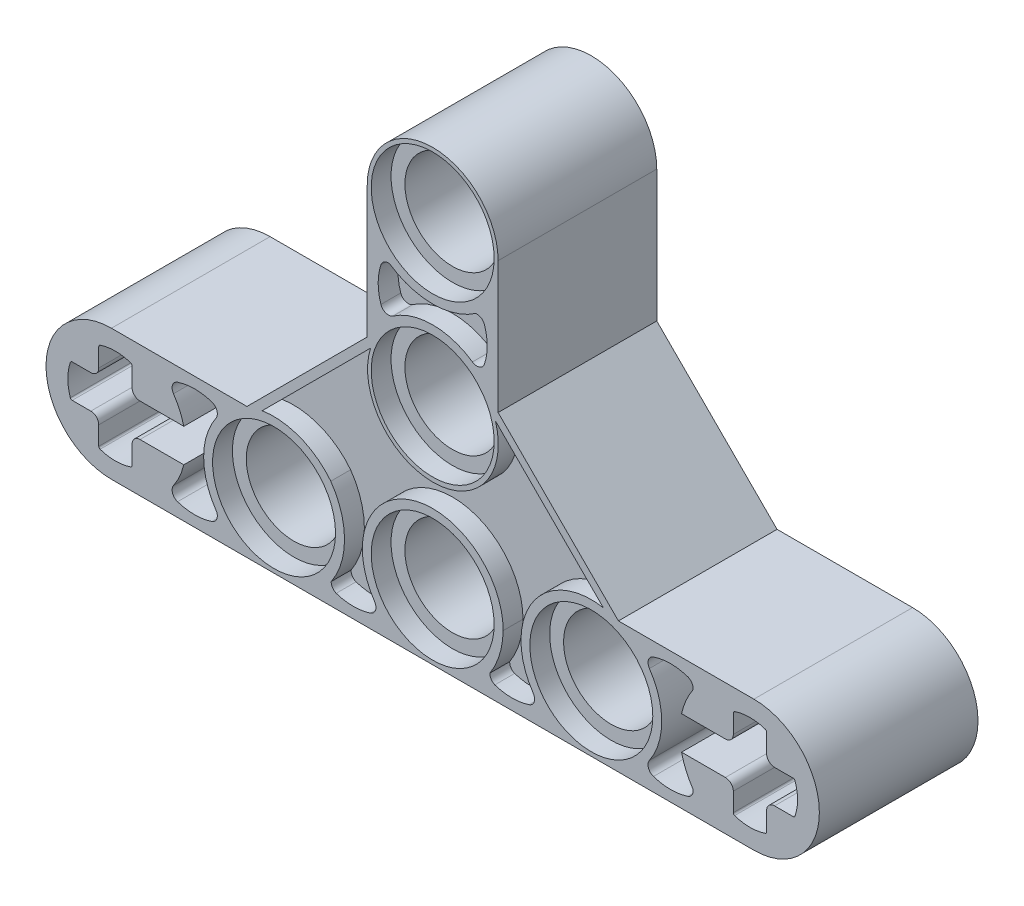
SolidWorks part; units mm, degrees
ref_plane "Front Plane" through (0, 0, 0) normal (0, 0, 1) x (1, 0, 0)
ref_plane "Top Plane" through (0, 0, 0) normal (0, 1, 0) x (1, 0, 0)
ref_plane "Right Plane" through (0, 0, 0) normal (1, 0, 0) x (0, 0, -1)
sketch "Sketch2" plane through (0, 0, 0) normal (0, 0, 1) x (1, 0, 0)
  line L0 (16.2, -3.3) -> (-16.2, -3.3)
  line L2 (16.2, 3.3) -> (9.3669, 3.3)
  line L6 (-17.24, 0.84) -> (-18.1777, 0.84)
  line L7 (-16.84, -2.1777) -> (-16.84, -1.24)
  line L8 (-15.16, -2.1777) -> (-15.16, -1.24)
  line L9 (-16.84, -2.2482) -> (-15.16, 2.2482) construction
  line L10 (-16.84, 2.2482) -> (-15.16, -2.2482) construction
  line L11 (-13.8223, 0.84) -> (-14.76, 0.84)
  line L12 (-13.8223, -0.84) -> (-14.76, -0.84)
  line L13 (-13.7518, 0.84) -> (-18.2482, -0.84) construction
  line L14 (-13.7518, -0.84) -> (-18.2482, 0.84) construction
  line L15 (-16.84, 1.24) -> (-16.84, 2.1777)
  line L16 (-15.16, 1.24) -> (-15.16, 2.1777)
  line L17 (-17.24, -0.84) -> (-18.1777, -0.84)
  line L18 (-13.7518, 0.84) -> (-12.5508, 0.84)
  line L19 (-13.7518, -0.84) -> (-12.5508, -0.84)
  line L20 (-13.8223, -0.84) -> (-13.7518, -0.84)
  line L21 (-13.8223, 0.84) -> (-13.7518, 0.84)
  line L22 (0, -55) -> (0, 55) construction
  line L23 (16.84, 1.24) -> (16.84, 2.1777)
  line L24 (15.16, 1.24) -> (15.16, 2.1777)
  line L25 (13.8223, 0.84) -> (14.76, 0.84)
  line L26 (13.8223, 0.84) -> (13.7518, 0.84)
  line L27 (13.7518, 0.84) -> (12.5508, 0.84)
  line L28 (13.7518, -0.84) -> (12.5508, -0.84)
  line L29 (13.8223, -0.84) -> (13.7518, -0.84)
  line L30 (13.8223, -0.84) -> (14.76, -0.84)
  line L31 (15.16, -2.1777) -> (15.16, -1.24)
  line L32 (16.84, -2.1777) -> (16.84, -1.24)
  line L33 (17.24, -0.84) -> (18.1777, -0.84)
  line L34 (17.24, 0.84) -> (18.1777, 0.84)
  line L38 (9.3669, 3.3) -> (3.3, 9.3669)
  line L40 (-16.2, 3.3) -> (-9.3669, 3.3)
  line L42 (3.3, 9.3669) -> (3.3, 16)
  line L45 (-3.3, 9.3669) -> (-3.3, 16)
  line L47 (-9.3669, 3.3) -> (-3.3, 9.3669)
  circle A0 centre (0, 0) radius 2.4
  circle A1 centre (8, 0) radius 2.4
  circle A2 centre (-8, 0) radius 2.4
  circle A3 centre (0, 8) radius 2.4
  circle A4 centre (0, 16) radius 2.4
  arc A5 (11.134, -2.6101) -> (12.866, -2.6101) centre (12, 0) ccw
  arc A6 (13.129, -2.1695) -> (12.866, -2.6101) centre (12.734, -2.2325) cw
  arc A7 (13.129, -2.1695) -> (13.129, 2.1695) centre (16.3, 0) cw
  arc A8 (13.129, 2.1695) -> (12.866, 2.6101) centre (12.734, 2.2325) ccw
  arc A9 (12.866, 2.6101) -> (11.134, 2.6101) centre (12, 0) ccw
  arc A10 (10.9299, 2.0046) -> (11.134, 2.6101) centre (11.26, 2.2304) cw
  arc A11 (10.9299, -2.0046) -> (10.9299, 2.0046) centre (8, 0) ccw
  arc A12 (10.9299, -2.0046) -> (11.134, -2.6101) centre (11.26, -2.2304) ccw
  arc A13 (-12.866, -2.6101) -> (-11.134, -2.6101) centre (-12, 0) ccw
  arc A14 (-10.9299, -2.0046) -> (-11.134, -2.6101) centre (-11.26, -2.2304) cw
  arc A15 (-10.9299, -2.0046) -> (-10.9299, 2.0046) centre (-8, 0) cw
  arc A16 (-10.9299, 2.0046) -> (-11.134, 2.6101) centre (-11.26, 2.2304) ccw
  arc A17 (-11.134, 2.6101) -> (-12.866, 2.6101) centre (-12, 0) ccw
  arc A18 (-13.0701, 2.0046) -> (-12.866, 2.6101) centre (-12.74, 2.2304) cw
  arc A19 (-13.0701, -2.0046) -> (-13.0701, 2.0046) centre (-16, 0) ccw
  arc A20 (-13.0701, -2.0046) -> (-12.866, -2.6101) centre (-12.74, -2.2304) ccw
  arc A21 (-13.7276, -0.7722) -> (-13.7276, 0.7722) centre (-16, 0) ccw construction
  arc A22 (-15.2278, 2.2724) -> (-16.7722, 2.2724) centre (-16, 0) ccw
  arc A23 (-18.2724, 0.7722) -> (-18.2724, -0.7722) centre (-16, 0) ccw
  arc A24 (-16.7722, -2.2724) -> (-15.2278, -2.2724) centre (-16, 0) ccw
  arc A25 (-16.84, -1.24) -> (-17.24, -0.84) centre (-17.24, -1.24) ccw
  arc A26 (-15.16, -1.24) -> (-14.76, -0.84) centre (-14.76, -1.24) cw
  arc A27 (-14.76, 0.84) -> (-15.16, 1.24) centre (-14.76, 1.24) cw
  arc A28 (-17.24, 0.84) -> (-16.84, 1.24) centre (-17.24, 1.24) ccw
  arc A29 (-18.1777, 0.84) -> (-18.2724, 0.7722) centre (-18.1777, 0.74) ccw
  arc A30 (-18.1777, -0.84) -> (-18.2724, -0.7722) centre (-18.1777, -0.74) cw
  arc A31 (-16.7722, -2.2724) -> (-16.84, -2.1777) centre (-16.74, -2.1777) cw
  arc A32 (-15.2278, -2.2724) -> (-15.16, -2.1777) centre (-15.26, -2.1777) ccw
  arc A33 (-13.7276, -0.7722) -> (-13.8223, -0.84) centre (-13.8223, -0.74) cw construction
  arc A34 (-13.8223, 0.84) -> (-13.7276, 0.7722) centre (-13.8223, 0.74) cw construction
  arc A35 (-15.2278, 2.2724) -> (-15.16, 2.1777) centre (-15.26, 2.1777) cw
  arc A36 (-16.84, 2.1777) -> (-16.7722, 2.2724) centre (-16.74, 2.1777) cw
  arc A50 (17.24, 0.84) -> (16.84, 1.24) centre (17.24, 1.24) cw
  arc A57 (16.84, 2.1777) -> (16.7722, 2.2724) centre (16.74, 2.1777) ccw
  arc A58 (-12.5508, -0.84) -> (-12.5508, 0.84) centre (-16, 0) ccw
  arc A59 (15.2278, 2.2724) -> (16.7722, 2.2724) centre (16, 0) cw
  arc A60 (15.2278, 2.2724) -> (15.16, 2.1777) centre (15.26, 2.1777) ccw
  arc A61 (14.76, 0.84) -> (15.16, 1.24) centre (14.76, 1.24) ccw
  arc A62 (12.5508, 0.84) -> (12.5508, -0.84) centre (16.3, 0) ccw
  arc A63 (15.16, -1.24) -> (14.76, -0.84) centre (14.76, -1.24) ccw
  arc A64 (15.2278, -2.2724) -> (15.16, -2.1777) centre (15.26, -2.1777) cw
  arc A65 (16.7722, -2.2724) -> (15.2278, -2.2724) centre (16, 0) cw
  arc A66 (16.7722, -2.2724) -> (16.84, -2.1777) centre (16.74, -2.1777) ccw
  arc A67 (16.84, -1.24) -> (17.24, -0.84) centre (17.24, -1.24) cw
  arc A68 (18.1777, -0.84) -> (18.2724, -0.7722) centre (18.1777, -0.74) ccw
  arc A69 (18.2724, 0.7722) -> (18.2724, -0.7722) centre (16, 0) cw
  arc A70 (18.1777, 0.84) -> (18.2724, 0.7722) centre (18.1777, 0.74) cw
  arc A90 (16.2, 3.3) -> (16.2, -3.3) centre (16.2, 0) cw
  arc A91 (-16.2, 3.3) -> (-16.2, -3.3) centre (-16.2, 0) ccw
  arc A92 (3.3, 16) -> (-3.3, 16) centre (0, 16) ccw
  point P140 (-8, 0)
  dimension "D1" = 4.8
  dimension "D6" = 3.3
  dimension "D8" = 6.6331
  dimension "D9" = 8.5799
  dimension "D11" = 3.3
  dimension "D13" = 3.3
  dimension "D5" = 4
  dimension "D7" = 8
  dimension "D10" = 6.8331
  dimension "D12" = 32.4
  dimension "D14" = 6.8331
  dimension "D15" = 8.5799
  dimension "D16" = 6.6331
  dimension "D2" = 2
  dimension "D3" = 2
  dimension "D4" = 3
extrude "Boss-Extrude1" add sketch "Sketch2" along normal mid plane 8
sketch "Sketch4" plane through (0, 0, 4) normal (0, 0, 1) x (1, 0, 0)
  circle A0 centre (0, 0) radius 3.1
  circle A1 centre (8, 0) radius 3.1
  circle A2 centre (-8, 0) radius 3.1
  circle A3 centre (0, 8) radius 3.1
  circle A4 centre (0, 16) radius 3.1
  dimension "D1" = 6.2
  dimension "D2" = 2
  dimension "D3" = 2
  dimension "D4" = 3
extrude "Cut-Extrude1" cut sketch "Sketch4" against normal blind 1
mirror "Mirror1" about plane through (0, 0, 0) normal (0, 0, 1) of "Cut-Extrude1"
sketch "Sketch5" plane through (0, 0, -4) normal (0, 0, -1) x (-1, 0, 0)
  line L7 (-8.6045, 3.4958) -> (-3.1659, 8.9345)
  line L8 (3.1323, 8.9646) -> (8.601, 3.4958)
  arc A0 (-4.866, -2.6101) -> (-3.134, -2.6101) centre (-4, 0) ccw
  arc A1 (-2.8834, -2.2208) -> (-3.134, -2.6101) centre (-3.283, -2.2389) cw
  arc A6 (-5.0719, -2.0072) -> (-5.0719, 2.002) centre (-8.0018, -0.0026) ccw
  arc A7 (-5.0719, -2.0072) -> (-4.866, -2.6101) centre (-4.74, -2.2304) ccw
  arc A8 (3.134, -2.6101) -> (4.866, -2.6101) centre (4, 0) ccw
  arc A9 (5.1166, -2.2208) -> (4.866, -2.6101) centre (4.717, -2.2389) cw
  arc A10 (5.1166, -2.2208) -> (5.1387, 2.1501) centre (8.2876, -0.0513) cw
  arc A15 (2.9281, -2.0072) -> (3.134, -2.6101) centre (3.26, -2.2304) ccw
  arc A20 (-3.1659, 8.9345) -> (3.1323, 8.9646) centre (-0.0122, 7.9754) ccw
  arc A21 (-8.6045, 3.4958) -> (-5.0719, 2.002) centre (-8.0018, -0.0026) cw
  arc A22 (-3.5545, -0.0303) -> (-2.8834, -2.2208) centre (0.5759, 0.0371) ccw
  arc A23 (5.1387, 2.1501) -> (8.601, 3.4958) centre (8.0213, -0.1395) cw
  arc A24 (-3.5545, -0.0303) -> (3.55, 0) centre (-0.0022, -0.0242) cw
  arc A25 (2.9281, -2.0072) -> (2.9281, 2.002) centre (-0.0018, -0.0026) ccw [skipped]
  arc A26 (3.55, 0) -> (2.9281, -2.0072) centre (-0.1032, 0.0319) cw
  arc A27 (2.6101, 11.134) -> (2.6101, 12.866) centre (0, 12) ccw
  arc A28 (2.1695, 13.129) -> (2.6101, 12.866) centre (2.2325, 12.734) cw
  arc A29 (2.1695, 13.129) -> (-2.1695, 13.129) centre (0, 16.3) cw
  arc A30 (-2.1695, 13.129) -> (-2.6101, 12.866) centre (-2.2325, 12.734) ccw
  arc A31 (-2.6101, 12.866) -> (-2.6101, 11.134) centre (0, 12) ccw
  arc A32 (-2.0046, 10.9299) -> (-2.6101, 11.134) centre (-2.2304, 11.26) cw
  arc A33 (2.0046, 10.9299) -> (-2.0046, 10.9299) centre (0, 8) ccw
  arc A34 (2.0046, 10.9299) -> (2.6101, 11.134) centre (2.2304, 11.26) ccw
  point P39 (-6.3004, 5.8008)
  point P42 (0, 0)
  point P50 (6.0506, 6.0506)
  dimension "D2" = 2
extrude "Cut-Extrude2" cut sketch "Sketch5" against normal blind 1
mirror "Mirror2" about plane through (0, 0, 0) normal (0, 0, 1) of "Cut-Extrude2"
